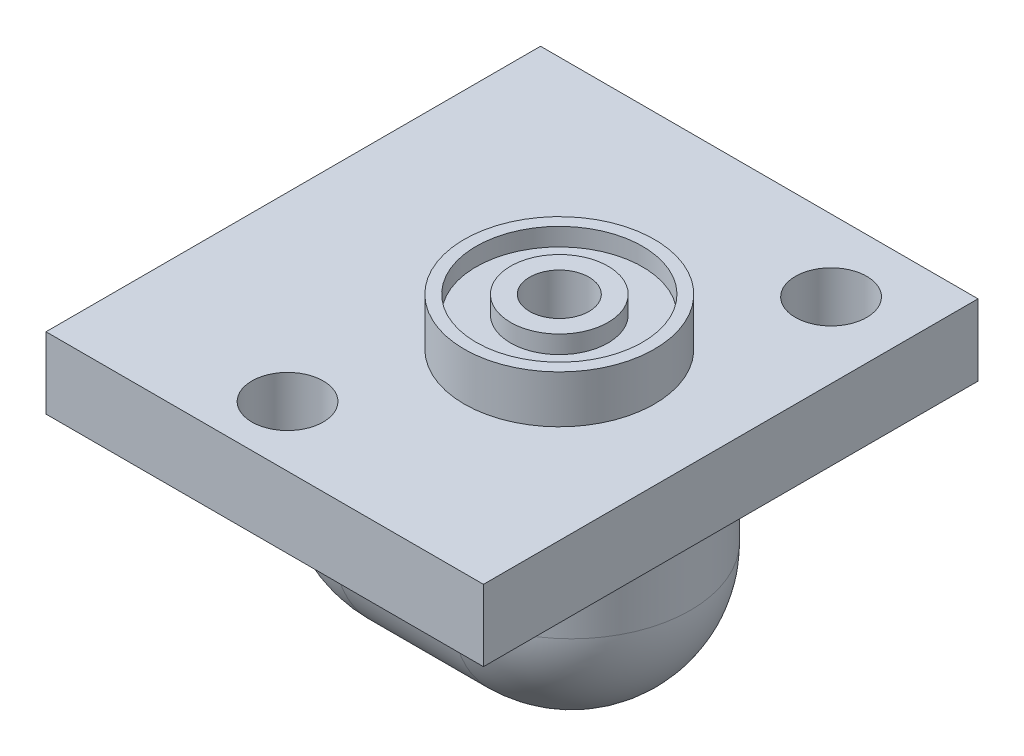
SolidWorks part; units mm, degrees
ref_plane "Front Plane" through (0, 0, 0) normal (0, 0, 1) x (1, 0, 0)
ref_plane "Top Plane" through (0, 0, 0) normal (0, 1, 0) x (1, 0, 0)
ref_plane "Right Plane" through (0, 0, 0) normal (1, 0, 0) x (0, 0, -1)
sketch "Sketch2" plane through (0, 0, 0) normal (0, 1, 0) x (1, 0, 0)
  line L1 (74.5852, 39.8007) -> (79.5852, 39.8007)
  line L2 (74.5852, 39.8007) -> (74.5852, 38.3007) construction
  line L3 (79.5852, 39.8007) -> (79.5852, 38.3007) construction
  line L4 (69.5852, 34.8007) -> (71.0852, 34.8007)
  line L6 (74.5852, 34.8007) -> (69.5852, 34.8007) construction
  line L8 (77.0852, 39.8007) -> (77.0852, 41.6641) construction
  line L9 (74.5852, 38.3007) -> (79.5852, 38.3007)
  line L10 (79.5852, 34.8007) -> (84.5852, 34.8007) construction
  line L11 (84.5852, 34.8007) -> (83.0852, 34.8007)
  arc A0 (69.5852, 34.8007) -> (74.5852, 39.8007) centre (74.5852, 34.8007) cw
  arc A5 (71.0852, 34.8007) -> (74.5852, 38.3007) centre (74.5852, 34.8007) cw
  arc A6 (84.5852, 34.8007) -> (79.5852, 39.8007) centre (79.5852, 34.8007) ccw
  arc A7 (83.0852, 34.8007) -> (79.5852, 38.3007) centre (79.5852, 34.8007) ccw
  dimension "D1" = 5
  dimension "D2" = 5
  dimension "D5" = 1.5
  dimension "D6" = 1.5
revolve "Revolve1" add sketch "Sketch2" angle 180 about L6
sketch "Sketch7" plane through (0, 0, 0) normal (0, 1, 0) x (1, 0, 0)
  line L0 (74.5852, 39.8007) -> (79.5852, 39.8007)
  line L1 (79.5852, 29.8007) -> (74.5852, 29.8007)
  line L2 (74.5852, 38.3007) -> (79.5852, 38.3007)
  line L3 (79.5852, 31.3007) -> (74.5852, 31.3007)
  arc A0 (79.5852, 39.8007) -> (84.5852, 34.8007) centre (79.5852, 34.8007) cw
  arc A1 (79.5852, 29.8007) -> (79.5852, 39.8007) centre (79.5852, 34.8007) ccw construction
  arc A2 (84.5852, 34.8007) -> (79.5852, 29.8007) centre (79.5852, 34.8007) cw
  arc A3 (74.5852, 29.8007) -> (69.5852, 34.8007) centre (74.5852, 34.8007) cw
  arc A4 (74.5852, 39.8007) -> (74.5852, 29.8007) centre (74.5852, 34.8007) ccw construction
  arc A5 (69.5852, 34.8007) -> (74.5852, 39.8007) centre (74.5852, 34.8007) cw
  arc A6 (79.5852, 38.3007) -> (83.0852, 34.8007) centre (79.5852, 34.8007) cw
  arc A7 (79.5852, 31.3007) -> (79.5852, 38.3007) centre (79.5852, 34.8007) ccw construction
  arc A8 (83.0852, 34.8007) -> (79.5852, 31.3007) centre (79.5852, 34.8007) cw
  arc A9 (74.5852, 31.3007) -> (71.0852, 34.8007) centre (74.5852, 34.8007) cw
  arc A10 (74.5852, 38.3007) -> (74.5852, 31.3007) centre (74.5852, 34.8007) ccw construction
  arc A11 (71.0852, 34.8007) -> (74.5852, 38.3007) centre (74.5852, 34.8007) cw
extrude "Boss-Extrude2" add sketch "Sketch7" along normal blind 4
sketch "Sketch8" plane through (0, 4, 0) normal (0, 1, 0) x (1, 0, 0)
  line L0 (77.0852, 38.3007) -> (77.0852, 34.8007) construction
  line L9 (79.5852, 38.3007) -> (74.5852, 38.3007) construction
  line L11 (67.8852, 45.2007) -> (86.2852, 45.2007)
  line L12 (67.8852, 45.2007) -> (67.8852, 24.4007)
  line L13 (67.8852, 24.4007) -> (86.2852, 24.4007)
  line L14 (86.2852, 45.2007) -> (86.2852, 24.4007)
  line L15 (67.8852, 45.2007) -> (86.2852, 24.4007) construction
  line L16 (67.8852, 24.4007) -> (86.2852, 45.2007) construction
  line L17 (67.8852, 24.4007) -> (75.5052, 24.4007)
  line L18 (67.8852, 24.4007) -> (67.8852, 26.9407)
  line L19 (67.8852, 26.9407) -> (75.5052, 26.9407)
  line L20 (75.5052, 24.4007) -> (75.5052, 26.9407)
  line L21 (67.8852, 24.4007) -> (79.3152, 24.4007)
  line L22 (67.8852, 24.4007) -> (67.8852, 34.5607)
  line L23 (67.8852, 34.5607) -> (79.3152, 34.5607)
  line L24 (79.3152, 24.4007) -> (79.3152, 34.5607)
  line L25 (67.8852, 24.4007) -> (83.1252, 24.4007)
  line L26 (67.8852, 24.4007) -> (67.8852, 42.1807)
  line L27 (67.8852, 42.1807) -> (83.1252, 42.1807)
  line L28 (83.1252, 24.4007) -> (83.1252, 42.1807)
  circle A0 centre (75.5052, 26.9407) radius 1.5
  circle A1 centre (79.3152, 34.5607) radius 2.9 construction
  circle A2 centre (83.1252, 42.1807) radius 1.5
  arc M22 (74.5852, 39.8007) -> (74.5852, 29.8007) centre (74.5852, 34.8007) ccw
  line M23 (74.5852, 29.8007) -> (79.5852, 29.8007)
  arc M24 (79.5852, 29.8007) -> (79.5852, 39.8007) centre (79.5852, 34.8007) ccw
  line M25 (79.5852, 39.8007) -> (74.5852, 39.8007)
  arc M26 (74.5852, 31.3007) -> (74.5852, 38.3007) centre (74.5852, 34.8007) cw
  line M27 (74.5852, 38.3007) -> (79.5852, 38.3007)
  arc M28 (79.5852, 38.3007) -> (79.5852, 31.3007) centre (79.5852, 34.8007) cw
  line M29 (79.5852, 31.3007) -> (74.5852, 31.3007)
  dimension "D5" = 3
  dimension "D8" = 5.8
  dimension "D11" = 3
  dimension "D1" = 20.8
  dimension "D2" = 18.4
  dimension "D3" = 2.54
  dimension "D4" = 7.62
  dimension "D6" = 10.16
  dimension "D7" = 11.43
  dimension "D9" = 17.78
  dimension "D10" = 15.24
extrude "Boss-Extrude4" add sketch "Sketch8" along normal blind 3 contours A2 L28 L13 L14 L11 L12 L27 M24 | A2 L27 L12 L23 L28 M22 M25 M24 | L28 L23 L24 M24 M25 M22 M26 M27 M28 M29 M23 | L28 M24 | L24 L23 M29 M28 M27 M26 | L24 L23 M23 M29 M26 M22 | L24 L23 M29 M26 | A0 L19 L12 L13 L20 | L13 L28 L24 M24 M23 | A0 L20 L13 L24 L23 L12 L19 M23 M22
sketch "Sketch12" plane through (0, 7, 0) normal (0, 1, 0) x (1, 0, 0)
  circle A0 centre (79.3152, 34.5607) radius 1.5
  circle A1 centre (79.3152, 34.5607) radius 4
  dimension "D1" = 3
  dimension "D2" = 8
extrude "Boss-Extrude5" add sketch "Sketch12" along normal blind 2 contours A1
sketch "Sketch13" plane through (0, 9, 0) normal (0, 1, 0) x (1, 0, 0)
  circle A0 centre (79.3152, 34.5607) radius 1.25
  dimension "D1" = 2.5
extrude "Cut-Extrude2" cut sketch "Sketch13" against normal up to next
sketch "Sketch14" plane through (0, 9, 0) normal (0, 1, 0) x (1, 0, 0)
  circle A1 centre (79.3152, 34.5607) radius 3.5
  circle A2 centre (79.3152, 34.5607) radius 2.05
  dimension "D1" = 4.1
  dimension "D2" = 7
extrude "Cut-Extrude3" cut sketch "Sketch14" against normal blind 0.75
hole_wizard "1/4 (0.25) Diameter Hole1" positions "3DSketch4" profile "Sketch19" hole size "1/4" standard "ANSI Inch"
sketch3d "3DSketch4"
  point P0 (77.0576, -5, -34.8007)
sketch "Sketch19" plane through (77.0576, -5, -34.8007) normal (1, 0, 0) x (0, 0, -1)
  line L0 (0, 0) -> (0, 5.9077)
  line L1 (0, 5.9077) -> (3.175, 4)
  line L2 (3.175, 4) -> (3.175, 0)
  line L5 (3.175, 0) -> (0, 0)
  line L10 (0, 5.9077) -> (-3.175, 4) construction
  line L11 (0, -6.35) -> (0, 107.95) construction
  dimension "Hole Dia." = 6.35
  dimension "Hole Depth" = 4
  dimension "Drill Angle" = 118
